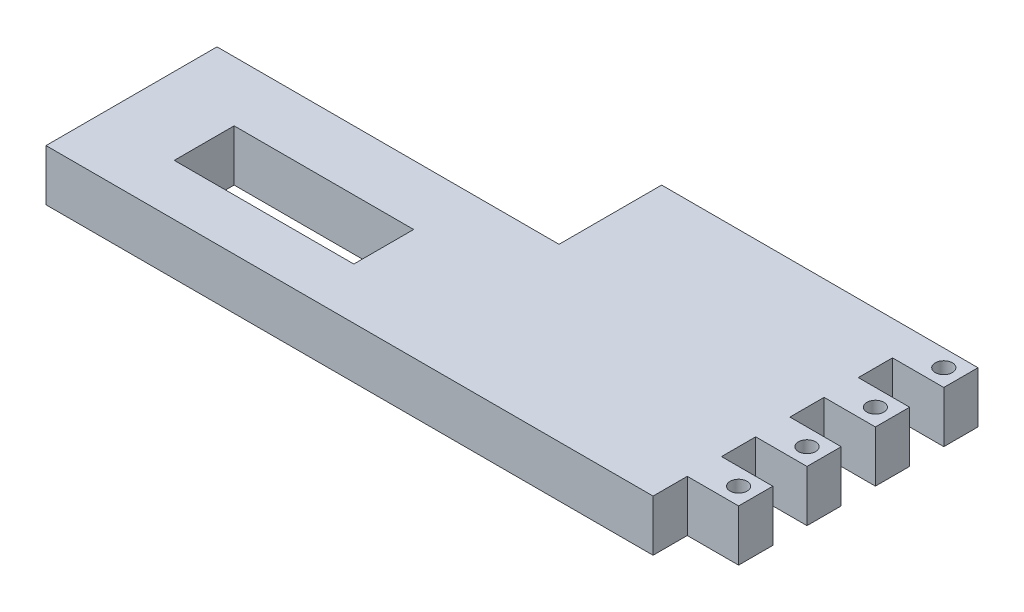
SolidWorks part; units mm, degrees
ref_plane "Front Plane" through (0, 0, 0) normal (0, 0, 1) x (1, 0, 0)
ref_plane "Top Plane" through (0, 0, 0) normal (0, 1, 0) x (1, 0, 0)
ref_plane "Right Plane" through (0, 0, 0) normal (1, 0, 0) x (0, 0, -1)
sketch "Sketch1" plane through (0, 0, 0) normal (0, 1, 0) x (1, 0, 0)
  line L0 (-40, 0) -> (0, 0)
  line L1 (0, 0) -> (0, 12)
  line L2 (0, 12) -> (37, 12)
  line L3 (37, 0) -> (37, 4)
  line L4 (37, 4) -> (31, 4)
  line L5 (31, 4) -> (31, 8)
  line L6 (31, 8) -> (37, 8)
  line L7 (37, 8) -> (37, 12)
  line L8 (31, -4) -> (37, -4)
  line L9 (37, -4) -> (37, -8)
  line L10 (37, -8) -> (31, -8)
  line L11 (31, -12) -> (31, -8)
  line L12 (37, 0) -> (31, 0)
  line L13 (31, 0) -> (31, -4)
  line L14 (31, -20) -> (-40, -20)
  line L15 (-40, -20) -> (-40, 0)
  line L16 (31, -12) -> (37, -12)
  line L17 (37, -12) -> (37, -16)
  line L18 (37, -16) -> (31, -16)
  line L19 (31, -16) -> (31, -20)
  dimension "D1" = 4
  dimension "D2" = 31
  dimension "D3" = 12
  dimension "D4" = 6
  dimension "D5" = 4
  dimension "D6" = 4
  dimension "D7" = 20
  dimension "D8" = 40
  dimension "D9" = 4
  dimension "D10" = 4
  dimension "D11" = 4
  dimension "D12" = 4
extrude "Boss-Extrude1" add sketch "Sketch1" along normal blind 6
sketch "Sketch2" plane through (0, 6, 0) normal (0, 1, 0) x (1, 0, 0)
  line L0 (0, 12) -> (0, 0) construction
  line L1 (-31, -7) -> (-10, -7)
  line L2 (-31, -7) -> (-31, -14)
  line L3 (-31, -14) -> (-10, -14)
  line L4 (-10, -7) -> (-10, -14)
  line L5 (-40, -20) -> (31, -20) construction
  dimension "D1" = 7
  dimension "D2" = 21
  dimension "D3" = 10
  dimension "D4" = 6
extrude "Cut-Extrude1" cut sketch "Sketch2" against normal through all
sketch "Sketch3" plane through (0, 6, 0) normal (0, 1, 0) x (1, 0, 0)
  line L0 (37, 8) -> (37, 12) construction
  line L1 (37, 0) -> (37, 4) construction
  line L2 (37, -8) -> (37, -4) construction
  line L3 (37, -16) -> (37, -12) construction
  circle A0 centre (35, 10) radius 1
  circle A1 centre (35, 2) radius 1
  circle A2 centre (35, -6) radius 1
  circle A3 centre (35, -14) radius 1
  point P4 (37, 10)
  point P13 (37, 2)
  point P16 (37, -6)
  point P19 (37, -14)
  dimension "D1" = 2
  dimension "D2" = 2
extrude "Cut-Extrude2" cut sketch "Sketch3" against normal through all
